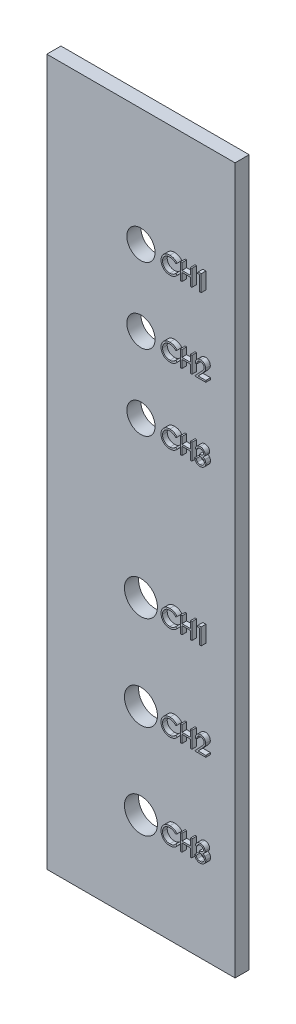
SolidWorks part; units mm, degrees
ref_plane "Front Plane" through (0, 0, 0) normal (0, 0, 1) x (1, 0, 0)
ref_plane "Top Plane" through (0, 0, 0) normal (0, 1, 0) x (1, 0, 0)
ref_plane "Right Plane" through (0, 0, 0) normal (1, 0, 0) x (0, 0, -1)
sketch "Sketch1" plane through (0, 0, 0) normal (0, 0, 1) x (1, 0, 0)
  line L0 (-20, 34) -> (20, 34) construction
  line L1 (-20, -75) -> (20, -75)
  line L2 (-20, -75) -> (-20, 75)
  line L3 (-20, 75) -> (20, 75)
  line L4 (20, -75) -> (20, 75)
  line L5 (-20, -75) -> (20, 75) construction
  line L6 (-20, 75) -> (20, -75) construction
  line L7 (0, 75) -> (0, -75) construction
  circle A1 centre (0, 34) radius 3
  circle A2 centre (0, 50) radius 3
  circle A3 centre (0, 18) radius 3
  circle A4 centre (0, -55) radius 3.5
  circle A5 centre (0, -35) radius 3.5
  circle A6 centre (0, -15) radius 3.5
  point P0 (0, 0)
  point P22 (0, 34)
  dimension "D3" = 6
  dimension "D9" = 7
  dimension "D1" = 150
  dimension "D2" = 40
  dimension "D5" = 16
  dimension "D6" = 16
  dimension "D8" = 25
  dimension "D10" = 20
  dimension "D11" = 20
  dimension "D12" = 20
extrude "Boss-Extrude1" add sketch "Sketch1" along normal blind 3
sketch "Sketch2" plane through (0, 0, 3) normal (0, 0, 1) x (1, 0, 0)
  line L0 (20, 75) -> (-20, 75) construction
  line L1 (-20, 75) -> (-20, -75) construction
  line L2 (-20, -75) -> (20, -75) construction
  text T0 "CH1"
  text T1 "CH2"
  text T2 "CH3"
  text T3 "CH1"
  text T4 "CH2\r\n"
  text T5 "CH3\r\n"
  dimension "D1" = 26.5
  dimension "D2" = 25
  dimension "D3" = 25
  dimension "D4" = 42.5
  dimension "D5" = 25
  dimension "D6" = 58.5
  dimension "D7" = 25
  dimension "D8" = 58.5
  dimension "D9" = 25
  dimension "D10" = 38.5
  dimension "D11" = 25
  dimension "D12" = 18.5
extrude "Boss-Extrude2" add sketch "Sketch2" along normal blind 1
